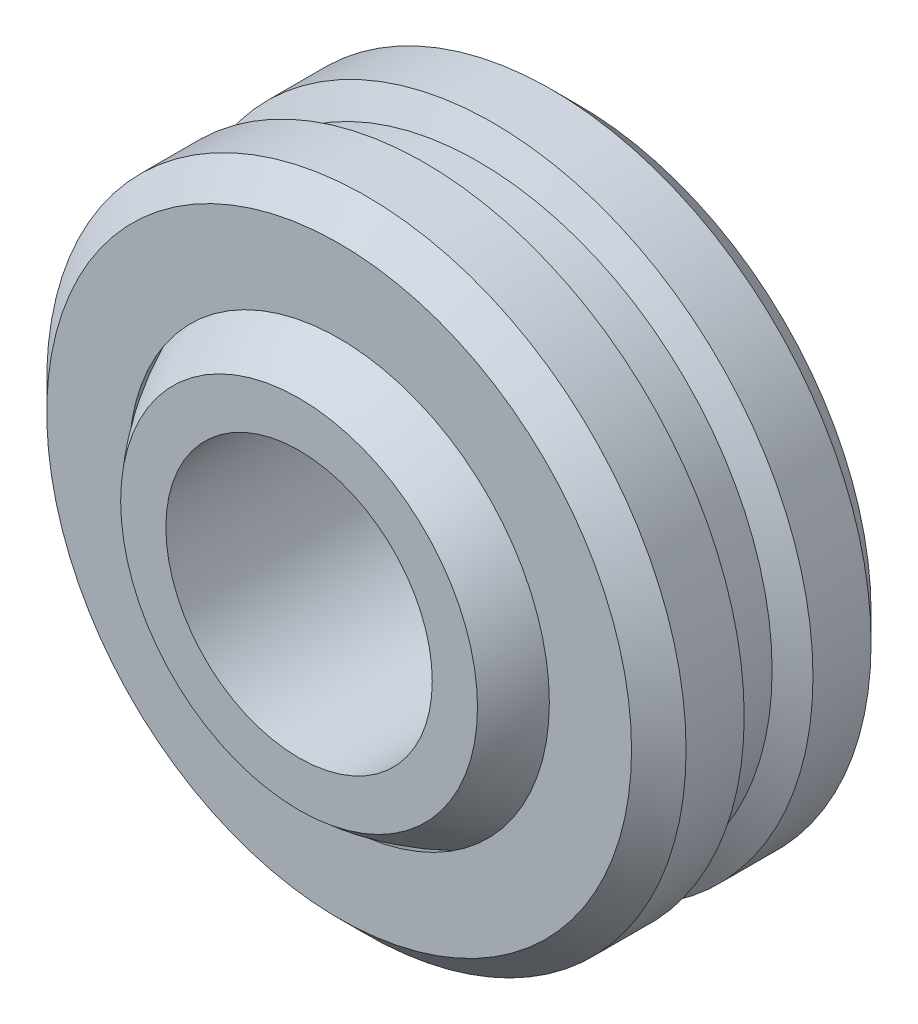
SolidWorks part; units mm, degrees
ref_plane "Front" through (0, 0, 0) normal (0, 0, 1) x (1, 0, 0)
ref_plane "Top" through (0, 0, 0) normal (0, 1, 0) x (1, 0, 0)
ref_plane "Right" through (0, 0, 0) normal (1, 0, 0) x (0, 0, -1)
sketch "Sketch1" plane through (0, 0, 0) normal (0, 0, 1) x (1, 0, 0)
  circle A0 centre (0, 0) radius 3.9688 construction
  circle A1 centre (0, 0) radius 7.1374 construction
  circle A2 centre (0, 0) radius 7.2088 construction
  circle A3 centre (0, 0) radius 9.525
  dimension "D OD" = 19.05
  dimension "B Hole Dia" = 7.9375
  dimension "Ball Dia" = 14.2748
  dimension "D1" = 14.4175
extrude "Extrude1" add sketch "Sketch1" along normal mid plane 7.1374
sketch "Sketch2" plane through (0, 0, 0) normal (0, 0, 1) x (1, 0, 0)
  line L0 (0, 7.2088) -> (0, -7.2088)
  line L1 (0, 7.2088) -> (0, 9.525) construction
  circle A0 centre (0, 0) radius 7.2088 construction
  arc A1 (0, -7.2088) -> (0, 7.2088) centre (0, 0) ccw
  circle A2 centre (0, 0) radius 9.525 construction
revolve "Cut-Revolve1" cut sketch "Sketch2" angle 360 about L1
sketch "Sketch3" plane through (0, 0, 0) normal (0, 0, 1) x (1, 0, 0)
  line L0 (0, 7.1374) -> (0, -7.1374)
  line L1 (0, 7.1374) -> (0, 9.525) construction
  circle A0 centre (0, 0) radius 7.1374 construction
  arc A1 (0, -7.1374) -> (0, 7.1374) centre (0, 0) ccw
  circle A2 centre (0, 0) radius 9.525 construction
revolve "Revolve1" add sketch "Sketch3" angle 360 about L1
sketch "Sketch4" plane through (0, 0, 0) normal (0, 0, 1) x (1, 0, 0)
  circle A0 centre (0, 0) radius 3.9688 construction
  circle A1 centre (0, 0) radius 3.9688
extrude "Cut-Extrude1" cut sketch "Sketch4" against normal through all and the other way through all
sketch "Sketch5" plane through (0, 0, 0) normal (1, 0, 0) x (0, 0, -1)
  line L0 (-4.7625, 9.525) -> (4.7625, 9.525) construction
  line L1 (-4.7625, 9.525) -> (-5.9322, 9.525)
  line L2 (-4.7625, 9.525) -> (-4.7625, -9.525)
  line L3 (-4.7625, -9.525) -> (-5.9322, -9.525)
  line L4 (-5.9322, 9.525) -> (-5.9322, -9.525)
  line L5 (4.7625, -9.525) -> (5.9322, -9.525)
  line L6 (4.7625, -9.525) -> (4.7625, 9.525)
  line L7 (4.7625, 9.525) -> (5.9322, 9.525)
  line L8 (5.9322, -9.525) -> (5.9322, 9.525)
  line L16 (3.5687, 9.525) -> (-3.5687, 9.525) construction
  line L17 (5.9322, -3.9688) -> (5.9322, 3.9688) construction
  line L18 (-5.9322, -3.9688) -> (-5.9322, 3.9688) construction
  line L19 (-4.7625, -9.525) -> (4.7625, -9.525) construction
  line L20 (-3.5687, -9.525) -> (3.5687, -9.525) construction
  line L21 (0, 0) -> (-4.7625, 1.0123) construction
  line L22 (0, 0) -> (-4.7625, -1.0123) construction
  dimension "W ball Width" = 9.525
  dimension "Mis Angle" = 24
extrude "Cut-Extrude2" cut sketch "Sketch5" against normal through all and the other way through all
chamfer "Chamfer1" distance 0.8128 angle 45 2 edges at (9.525, 0, 3.5687) (9.525, 0, -3.5687)
sketch "Sketch7" plane through (0, 0, 0) normal (1, 0, 0) x (0, 0, -1)
  line L0 (0, 0) -> (-4.7625, -1.0123) construction
  line L1 (0, 0) -> (-4.7625, 1.0123) construction
  line L2 (0, 0) -> (-4.7625, -1.0123) construction
  line L3 (0, 0) -> (-4.7625, 1.0123) construction
sketch "Sketch8" plane through (0, 0, 0) normal (1, 0, 0) x (0, 0, -1)
  line L0 (-1.0248, 9.525) -> (-0.5791, 8.7529)
  line L1 (-0.5791, 8.7529) -> (0.5791, 8.7529)
  line L2 (0.5791, 8.7529) -> (1.0248, 9.525)
  line L3 (-1.0248, 9.525) -> (1.0248, 9.525)
  line L4 (2.7559, 9.525) -> (-2.7559, 9.525) construction
  line L5 (0, 0) -> (0, 8.7529) construction
  line L6 (0, 0) -> (4.7625, 0) construction
  line L7 (4.7625, -5.3161) -> (4.7625, 5.3161) construction
  line L8 (0, 7.2088) -> (0, 9.525) construction
  arc A0 (3.5687, 6.2634) -> (-3.5687, 6.2634) centre (0, 0) ccw construction
  dimension "D1" = 60
  dimension "D2" = 2.3162
  dimension "D3" = 0.7721
  dimension "D4" = 1.1581
revolve "Cut-Revolve2" cut sketch "Sketch8" angle 360 about L6
equation "\"D1@Sketch1\"=\"Ball Dia@Sketch1\"*1.01"
equation "\"D3@Sketch8\" = \"D2@Sketch8\"/3"
equation "\"D4@Sketch8\" = \"D3@Sketch8\"*1.5"
